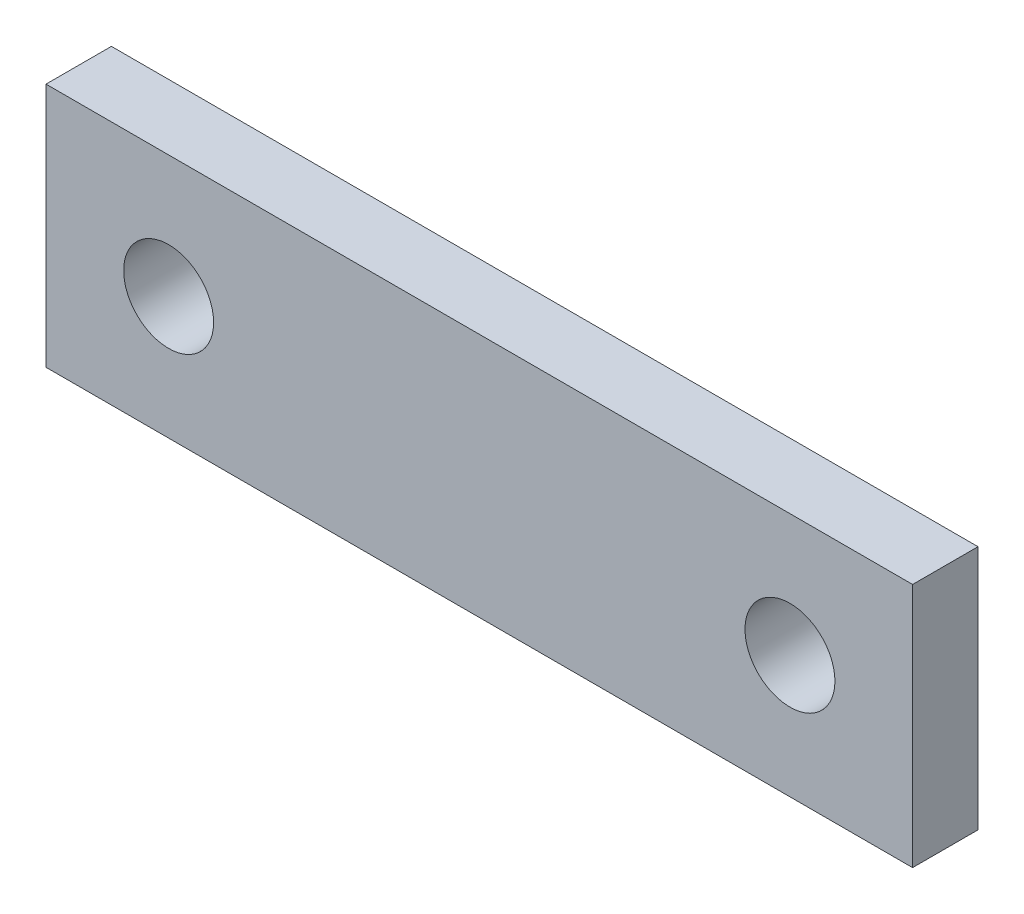
SolidWorks part; units mm, degrees
ref_plane "前视基准面" through (0, 0, 0) normal (0, 0, 1) x (1, 0, 0)
ref_plane "上视基准面" through (0, 0, 0) normal (0, 1, 0) x (1, 0, 0)
ref_plane "右视基准面" through (0, 0, 0) normal (1, 0, 0) x (0, 0, -1)
sketch "草图1" plane through (0, 0, 0) normal (0, 0, 1) x (1, 0, 0)
  line L1 (0, 0) -> (212, 0)
  line L2 (0, 0) -> (0, 60)
  line L3 (0, 60) -> (212, 60)
  line L4 (212, 0) -> (212, 60)
  dimension "D1" = 212
  dimension "D2" = 60
extrude "拉伸1" add sketch "草图1" along normal blind 16
sketch "草图2" plane through (0, 0, 16) normal (0, 0, 1) x (1, 0, 0)
  line L0 (0, 30) -> (212, 30) construction
  line L1 (0, 60) -> (0, 0) construction
  line L2 (212, 0) -> (212, 60) construction
  line L3 (106, 60) -> (106, 0) construction
  line L4 (212, 60) -> (0, 60) construction
  line L5 (0, 0) -> (212, 0) construction
  circle A0 centre (30, 30) radius 11
  circle A1 centre (182, 30) radius 11
  dimension "D3" = 22
  dimension "D1" = 76
  dimension "D2" = 152
extrude "拉伸2" cut sketch "草图2" against normal through all
